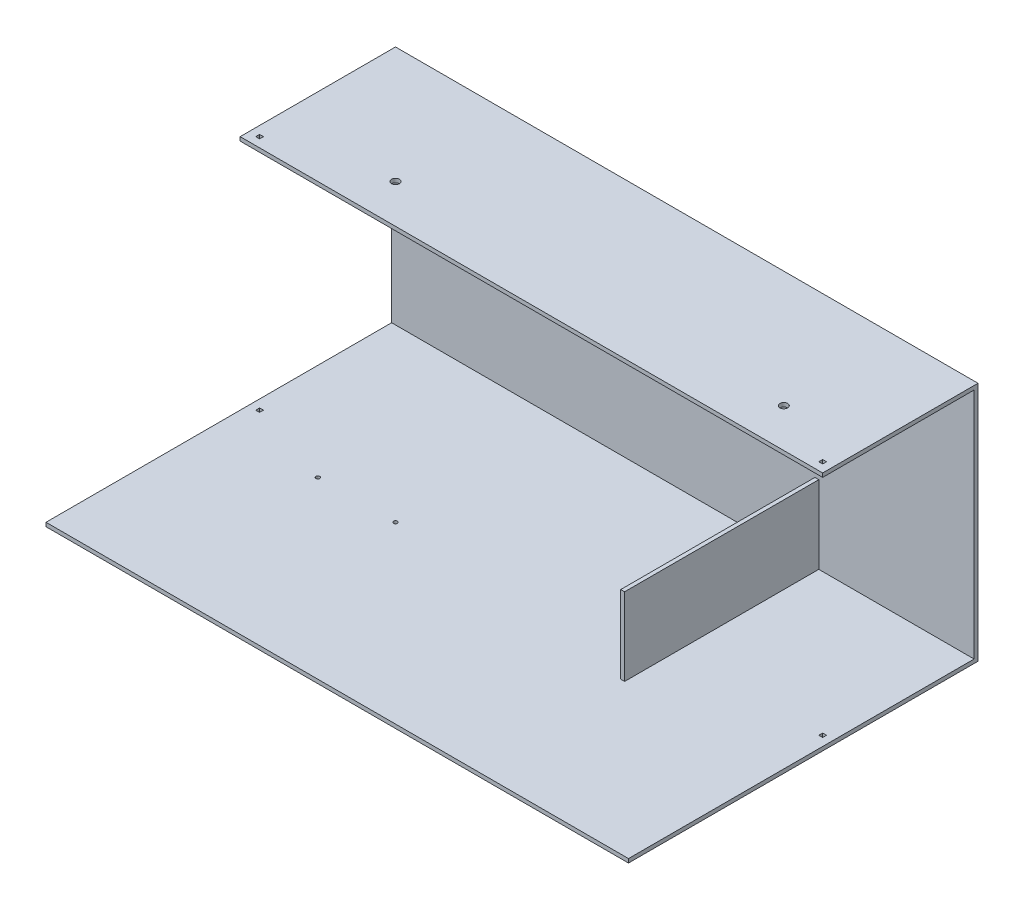
SolidWorks part; units mm, degrees
ref_plane "Front Plane" through (0, 0, 0) normal (0, 0, 1) x (1, 0, 0)
ref_plane "Top Plane" through (0, 0, 0) normal (0, 1, 0) x (1, 0, 0)
ref_plane "Right Plane" through (0, 0, 0) normal (1, 0, 0) x (0, 0, -1)
sketch "Sketch1" plane through (0, 0, 0) normal (0, 1, 0) x (1, 0, 0)
  line L1 (-375, 225) -> (375, 225)
  line L2 (-375, 225) -> (-375, -225)
  line L3 (-375, -225) -> (375, -225)
  line L4 (375, 225) -> (375, -225)
  line L5 (-375, 225) -> (375, -225) construction
  line L6 (-375, -225) -> (375, 225) construction
  point P0 (0, 0)
  dimension "D1" = 750
  dimension "D2" = 450
extrude "Boss-Extrude1" add sketch "Sketch1" along normal blind 310
sketch "Sketch7" plane through (0, 310, 0) normal (0, 1, 0) x (1, 0, 0)
  line L0 (375, 225) -> (-375, 225) construction
  line L1 (-370, 220) -> (370, 220)
  line L2 (-370, 220) -> (-370, -180)
  line L3 (-370, -180) -> (370, -180)
  line L4 (370, 220) -> (370, -180)
  line L5 (-370, 220) -> (370, -180) construction
  line L6 (-370, -180) -> (370, 220) construction
  point P0 (0, 0)
  dimension "D1" = 740
  dimension "D2" = 400
  dimension "D3" = 5
sketch "Sketch8" plane through (0, 0, 225) normal (0, 0, 1) x (1, 0, 0)
  line L0 (-375, 310) -> (-375, 0) construction
  line L1 (-375, 305) -> (375, 305)
  line L2 (-375, 305) -> (-375, 5)
  line L3 (-375, 5) -> (375, 5)
  line L4 (375, 305) -> (375, 5)
  line L5 (-375, 0) -> (375, 0) construction
  dimension "D1" = 750
  dimension "D2" = 300
  dimension "D3" = 0
  dimension "D4" = 5
extrude "Cut-Extrude1" cut sketch "Sketch8" against normal blind 445
sketch "Sketch10" plane through (0, 5, 0) normal (0, 1, 0) x (1, 0, 0)
  line L0 (-375, 225) -> (-375, -225) construction
  line L1 (375, 225) -> (-375, 225) construction
  circle A0 centre (-250, 0) radius 2.5
  circle A1 centre (-150, 0) radius 2.5
  dimension "D1" = 5
  dimension "D2" = 5
  dimension "D3" = 100
  dimension "D4" = 125
  dimension "D5" = 225
sketch "Sketch15" plane through (0, 5, 0) normal (0, 1, 0) x (1, 0, 0)
  line L0 (-375, 220) -> (375, 220) construction
  line L1 (170, 220) -> (175, 220)
  line L2 (170, 220) -> (170, -30)
  line L3 (170, -30) -> (175, -30)
  line L4 (175, 220) -> (175, -30)
  line L5 (375, 220) -> (375, -225) construction
  dimension "D1" = 250
  dimension "D2" = 5
  dimension "D3" = 200
extrude "Boss-Extrude8" add sketch "Sketch15" along normal blind 100
sketch "Sketch16" plane through (0, 310, 0) normal (0, 1, 0) x (1, 0, 0)
  line L0 (375, -225) -> (375, 225) construction
  line L1 (375, 225) -> (-375, 225) construction
  line L3 (375, 25) -> (-375, 25)
  line L4 (375, 25) -> (375, -225)
  line L5 (375, -225) -> (-375, -225)
  line L6 (-375, 25) -> (-375, -225)
  circle A0 centre (275, 75) radius 5
  circle A1 centre (-225, 75) radius 5
  dimension "D1" = 10
  dimension "D3" = 10
  dimension "D2" = 500
  dimension "D4" = 100
  dimension "D5" = 150
  dimension "D6" = 250
extrude "Cut-Extrude2" cut sketch "Sketch16" against normal blind 10 and the other way through all
sketch "Sketch18" plane through (0, 310, 0) normal (0, 1, 0) x (1, 0, 0)
  line L0 (375, 25) -> (-375, 25) construction
  line L1 (-365, 40) -> (-360, 40)
  line L2 (-365, 40) -> (-365, 35)
  line L3 (-365, 35) -> (-360, 35)
  line L4 (-360, 40) -> (-360, 35)
  line L5 (-375, 225) -> (-375, 25) construction
  line L6 (375, 25) -> (375, 225) construction
  line L7 (360, 40) -> (365, 40)
  line L8 (360, 40) -> (360, 35)
  line L9 (360, 35) -> (365, 35)
  line L10 (365, 40) -> (365, 35)
  point P12 (362.5, 35)
  dimension "D1" = 5
  dimension "D2" = 5
  dimension "D3" = 10
  dimension "D4" = 10
  dimension "D5" = 5
  dimension "D6" = 5
  dimension "D7" = 10
  dimension "D8" = 10
extrude "Cut-Extrude3" cut sketch "Sketch18" against normal through all
extrude "Cut-Extrude4" cut sketch "Sketch10" against normal through all
